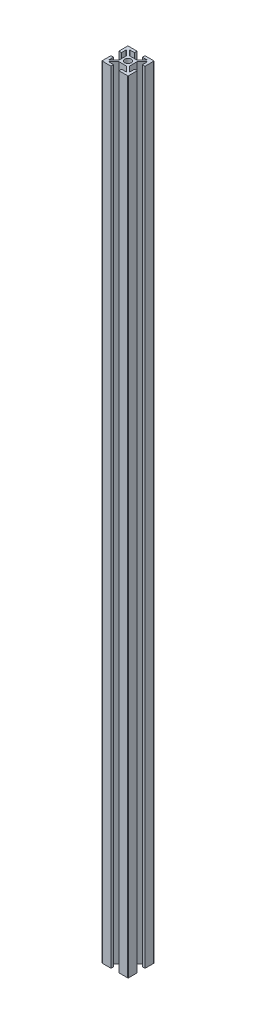
SolidWorks part; units mm, degrees
ref_plane "Front Plane" through (0, 0, 0) normal (0, 0, 1) x (1, 0, 0)
ref_plane "Top Plane" through (0, 0, 0) normal (0, 1, 0) x (1, 0, 0)
ref_plane "Right Plane" through (0, 0, 0) normal (1, 0, 0) x (0, 0, -1)
sketch "Sketch1" plane through (0, 0, 0) normal (0, 1, 0) x (1, 0, 0)
  line L0 (-9.8963, 3) -> (-8.1963, 3)
  line L3 (-3.1963, 10) -> (-9.6963, 10)
  line L4 (-10.0463, 3.15) -> (-10.0463, 9.65)
  line L7 (2.9332, 4) -> (-2.9332, 4)
  line L8 (-4, -2.9454) -> (-4, 2.9454)
  line L9 (-8.0463, 3.15) -> (-8.0463, 6.5862)
  line L10 (-6.6144, 8) -> (-3.1963, 8)
  line L11 (-3.0463, 8.15) -> (-3.0463, 9.85)
  line L12 (-8.0463, 8) -> (-4, 4) construction
  line L13 (-7.7908, 6.6929) -> (-4, 2.9454)
  line L14 (-6.7198, 7.7433) -> (-2.9332, 4)
  line L15 (8.0463, 8) -> (4, 4) construction
  line L22 (0, 0) -> (0, 11.6886) construction
  line L25 (0, 0) -> (-14.9841, 0) construction
  line L27 (6.7198, 7.7433) -> (2.9332, 4)
  line L28 (7.7908, 6.6929) -> (4, 2.9454)
  line L46 (3.0463, 8.15) -> (3.0463, 9.85)
  line L47 (6.6144, 8) -> (3.1963, 8)
  line L48 (8.0463, 3.15) -> (8.0463, 6.5862)
  line L49 (4, -2.9454) -> (4, 2.9454)
  line L50 (10.0463, 3.15) -> (10.0463, 9.65)
  line L51 (3.1963, 10) -> (9.6963, 10)
  line L52 (9.8963, 3) -> (8.1963, 3)
  line L53 (8.0463, -8) -> (4, -4) construction
  line L54 (-8.0463, -8) -> (-4, -4) construction
  line L55 (9.8963, -3) -> (8.1963, -3)
  line L56 (3.1963, -10) -> (9.6963, -10)
  line L57 (10.0463, -3.15) -> (10.0463, -9.65)
  line L58 (8.0463, -3.15) -> (8.0463, -6.5862)
  line L59 (6.6144, -8) -> (3.1963, -8)
  line L60 (3.0463, -8.15) -> (3.0463, -9.85)
  line L61 (7.7908, -6.6929) -> (4, -2.9454)
  line L62 (6.7198, -7.7433) -> (2.9332, -4)
  line L63 (-6.7198, -7.7433) -> (-2.9332, -4)
  line L64 (-7.7908, -6.6929) -> (-4, -2.9454)
  line L65 (-3.0463, -8.15) -> (-3.0463, -9.85)
  line L66 (-6.6144, -8) -> (-3.1963, -8)
  line L67 (-8.0463, -3.15) -> (-8.0463, -6.5862)
  line L68 (2.9332, -4) -> (-2.9332, -4)
  line L69 (-10.0463, -3.15) -> (-10.0463, -9.65)
  line L70 (-3.1963, -10) -> (-9.6963, -10)
  line L71 (-9.8963, -3) -> (-8.1963, -3)
  circle A0 centre (0, 0) radius 2.5
  arc A1 (-10.0463, 9.65) -> (-9.6963, 10) centre (-9.6963, 9.65) cw
  arc A2 (-9.8963, 3) -> (-10.0463, 3.15) centre (-9.8963, 3.15) cw
  arc A3 (-8.1963, 3) -> (-8.0463, 3.15) centre (-8.1963, 3.15) ccw
  arc A4 (-3.1963, 10) -> (-3.0463, 9.85) centre (-3.1963, 9.85) cw
  arc A5 (-3.1963, 8) -> (-3.0463, 8.15) centre (-3.1963, 8.15) ccw
  arc A6 (-6.7198, 7.7433) -> (-6.6144, 8) centre (-6.6144, 7.85) cw
  arc A7 (-7.7908, 6.6929) -> (-8.0463, 6.5862) centre (-7.8963, 6.5862) ccw
  arc A8 (7.7908, 6.6929) -> (8.0463, 6.5862) centre (7.8963, 6.5862) cw
  arc A9 (6.7198, 7.7433) -> (6.6144, 8) centre (6.6144, 7.85) ccw
  arc A10 (3.1963, 8) -> (3.0463, 8.15) centre (3.1963, 8.15) cw
  arc A11 (3.1963, 10) -> (3.0463, 9.85) centre (3.1963, 9.85) ccw
  arc A12 (8.1963, 3) -> (8.0463, 3.15) centre (8.1963, 3.15) cw
  arc A13 (9.8963, 3) -> (10.0463, 3.15) centre (9.8963, 3.15) ccw
  arc A14 (10.0463, 9.65) -> (9.6963, 10) centre (9.6963, 9.65) ccw
  arc A15 (10.0463, -9.65) -> (9.6963, -10) centre (9.6963, -9.65) cw
  arc A16 (9.8963, -3) -> (10.0463, -3.15) centre (9.8963, -3.15) cw
  arc A17 (8.1963, -3) -> (8.0463, -3.15) centre (8.1963, -3.15) ccw
  arc A18 (3.1963, -10) -> (3.0463, -9.85) centre (3.1963, -9.85) cw
  arc A19 (3.1963, -8) -> (3.0463, -8.15) centre (3.1963, -8.15) ccw
  arc A20 (6.7198, -7.7433) -> (6.6144, -8) centre (6.6144, -7.85) cw
  arc A21 (7.7908, -6.6929) -> (8.0463, -6.5862) centre (7.8963, -6.5862) ccw
  arc A22 (-7.7908, -6.6929) -> (-8.0463, -6.5862) centre (-7.8963, -6.5862) cw
  arc A23 (-6.7198, -7.7433) -> (-6.6144, -8) centre (-6.6144, -7.85) ccw
  arc A24 (-3.1963, -8) -> (-3.0463, -8.15) centre (-3.1963, -8.15) cw
  arc A25 (-3.1963, -10) -> (-3.0463, -9.85) centre (-3.1963, -9.85) ccw
  arc A26 (-8.1963, -3) -> (-8.0463, -3.15) centre (-8.1963, -3.15) cw
  arc A27 (-9.8963, -3) -> (-10.0463, -3.15) centre (-9.8963, -3.15) ccw
  arc A28 (-10.0463, -9.65) -> (-9.6963, -10) centre (-9.6963, -9.65) ccw
  point P8 (-10.0463, 10)
  point P27 (-10.0463, 3)
  point P30 (3.0463, 8)
  point P31 (10.0463, -10)
  point P50 (4, 0)
  point P55 (-8.0463, 3)
  point P58 (-3.0463, 10)
  point P61 (-3.0463, 8)
  point P63 (0, 4)
  point P65 (3.0463, 10)
  point P66 (8.0463, 3)
  point P67 (10.0463, 3)
  point P68 (10.0463, 10)
  point P118 (-4, 0)
  point P119 (10.0463, -3)
  point P120 (8.0463, -3)
  point P121 (3.0463, -10)
  point P122 (0, -4)
  point P123 (-3.0463, -8)
  point P124 (-3.0463, -10)
  point P125 (-8.0463, -3)
  point P126 (3.0463, -8)
  point P127 (-10.0463, -3)
  point P128 (-10.0463, -10)
  dimension "D2" = 0.35
  dimension "D3" = 0.15
  dimension "D4" = 0.15
  dimension "D5" = 0.15
  dimension "D12" = 0.15
  dimension "D13" = 0.15
  dimension "D14" = 0.15
  dimension "D6" = 2
  dimension "D7" = 7
  dimension "D8" = 7
  dimension "D9" = 2
  dimension "D10" = 0.75
  dimension "D11" = 0.75
extrude "Boss-Extrude2" add sketch "Sketch1" along normal blind 600
